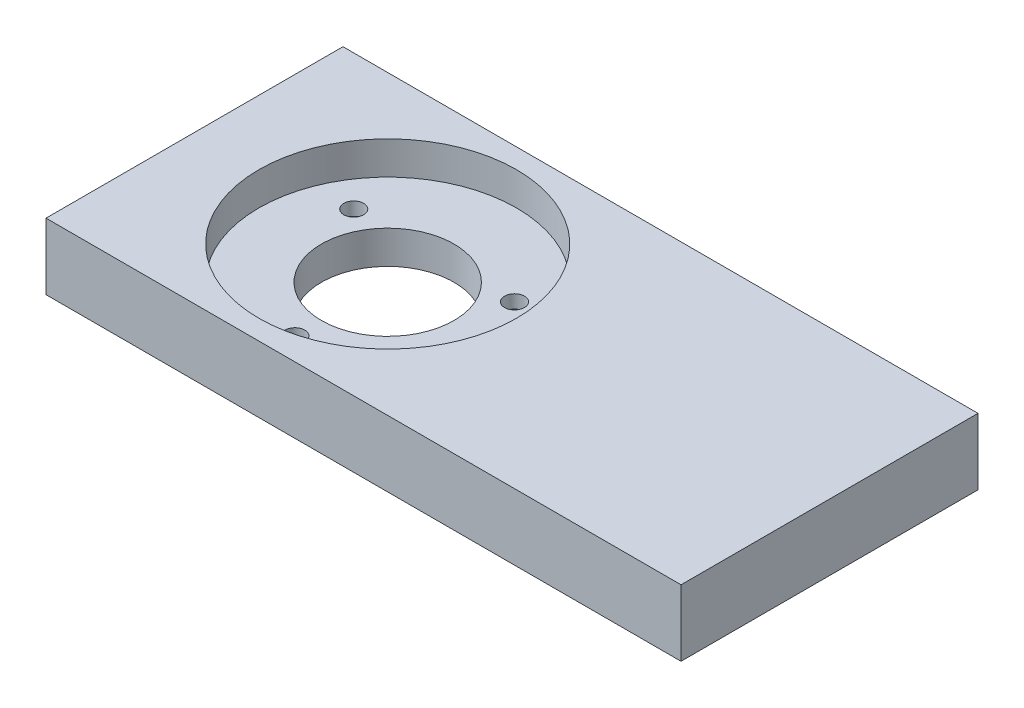
SolidWorks part; units mm, degrees
ref_plane "Front Plane" through (0, 0, 0) normal (0, 0, 1) x (1, 0, 0)
ref_plane "Top Plane" through (0, 0, 0) normal (0, 1, 0) x (1, 0, 0)
ref_plane "Right Plane" through (0, 0, 0) normal (1, 0, 0) x (0, 0, -1)
sketch "EncoderSideWallSketch" plane through (0, 0, 0) normal (0, 1, 0) x (1, 0, 0)
  line L1 (-39.2268, 22.7589) -> (56.5732, 22.7589)
  line L2 (-39.2268, 22.7589) -> (-39.2268, -22.0411)
  line L3 (-39.2268, -22.0411) -> (56.5732, -22.0411)
  line L4 (56.5732, 22.7589) -> (56.5732, -22.0411)
  dimension "D1" = 95.8
  dimension "D2" = 44.8
extrude "Boss-Extrude1" add sketch "EncoderSideWallSketch" along normal blind 10
sketch "Sketch2" plane through (0, 10, 0) normal (0, 1, 0) x (1, 0, 0)
  line L0 (8.6732, 22.7589) -> (8.6732, -22.0411) construction
  line L1 (56.5732, 22.7589) -> (-39.2268, 22.7589) construction
  line L2 (-39.2268, -22.0411) -> (56.5732, -22.0411) construction
  line L3 (-39.2268, 0.3589) -> (68.0487, 0.3589) construction
  line L4 (-39.2268, 22.7589) -> (-39.2268, -22.0411) construction
  circle A0 centre (-10.0768, 0.3589) radius 10
  dimension "D1" = 20
  dimension "D2" = 18.75
extrude "EncoderAxleCut" cut sketch "Sketch2" against normal blind 10
sketch "EncoderFullHole" plane through (0, 10, 0) normal (0, 1, 0) x (1, 0, 0)
  line L4 (-39.2268, 0.3589) -> (78.7836, 0.3589) construction
  line L5 (-39.2268, 22.7589) -> (-39.2268, -22.0411) construction
  circle A0 centre (-10.0768, 0.3589) radius 19.425
  dimension "D1" = 38.85
extrude "EncoderFullHoleBore" cut sketch "EncoderFullHole" against normal blind 5
sketch "EncoderScrewLayoutSketch" plane through (0, 5, 0) normal (0, 1, 0) x (1, 0, 0)
  line L0 (-22.2018, 7.3593) -> (2.0482, 7.3593) construction
  line L1 (2.0482, 7.3593) -> (-10.0768, -13.6418) construction
  line L2 (-10.0768, -13.6418) -> (-22.2018, 7.3593) construction
  line L3 (2.0482, 7.3593) -> (-16.1393, -3.1412) construction
  line L4 (-22.2018, 7.3593) -> (-4.0143, -3.1412) construction
  line L5 (-10.0768, 7.3593) -> (-10.0768, -13.6418) construction
  circle A0 centre (-10.0768, 0.3589) radius 10 construction
  circle A1 centre (-22.2018, 7.3593) radius 1.5
  circle A2 centre (2.0482, 7.3593) radius 1.5
  circle A3 centre (-10.0768, -13.6418) radius 1.5
  point P6 (-10.0768, 0.3589)
  dimension "D2" = 3
  dimension "D1" = 24.25
extrude "EncoderScrewLayout" cut sketch "EncoderScrewLayoutSketch" against normal through all
sketch "Sketch6" plane through (0, 0, 0) normal (0, -1, 0) x (1, 0, 0)
  circle A0 centre (-10.0768, 13.6418) radius 3
  circle A1 centre (-22.2018, -7.3593) radius 3
  circle A2 centre (2.0482, -7.3593) radius 3
  dimension "D1" = 6
extrude "Cut-Extrude4" cut sketch "Sketch6" against normal blind 3
